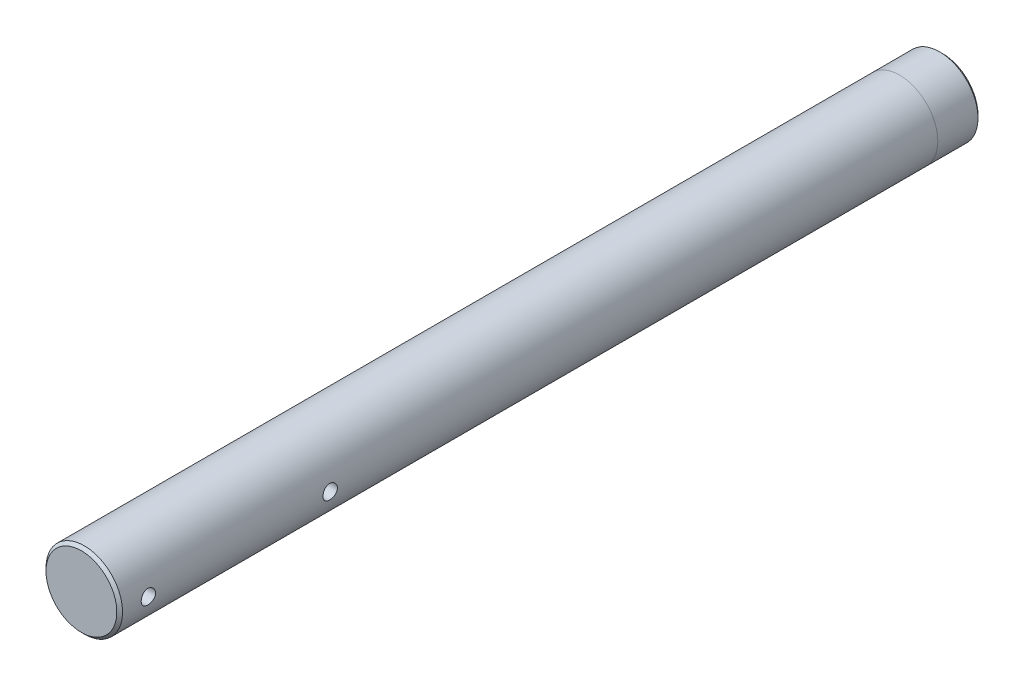
SolidWorks part; units mm, degrees
material "7075-T6, Plate (SS)"
ref_plane "Front" through (0, 0, 0) normal (0, 0, 1) x (1, 0, 0)
ref_plane "Top" through (0, 0, 0) normal (0, 1, 0) x (1, 0, 0)
ref_plane "Right" through (0, 0, 0) normal (1, 0, 0) x (0, 0, -1)
sketch "Sketch1" plane through (0, 0, 0) normal (1, 0, 0) x (0, 0, -1)
  line L0 (0, 4) -> (0, 0) construction
  line L1 (0, 0) -> (59.0815, 0) construction
  line L3 (-45, 4) -> (45, 4)
  line L4 (-45, 4) -> (-45, 0)
  line L5 (-45, 0) -> (45, 0)
  line L6 (45, 4) -> (45, 0)
  dimension "D1" = 8
  dimension "D2" = 90
revolve "Revolve1" add sketch "Sketch1" angle 360 about L1
chamfer "Chamfer1" distance 0.3 angle 45 2 edges at (4, 0, -45) (4, 0, 45)
sketch "Sketch6" plane through (0, 0, 0) normal (1, 0, 0) x (0, 0, -1)
  line L0 (45, 0) -> (-45, 0) construction
  line L1 (45, -3.7) -> (45, 3.7) construction
  line L2 (-45, 3.7) -> (-45, -3.7) construction
  circle A2 centre (-23, 0) radius 0.75
  circle A3 centre (-42, 0) radius 0.75
  dimension "D1" = 1.5
  dimension "D2" = 22
  dimension "D5" = 3
extrude "Cut-Extrude1" cut sketch "Sketch6" against normal through all both and the other way through all
sketch "Sketch7" plane through (0, 0, 0) normal (1, 0, 0) x (0, 0, -1)
  line L0 (40.5, 13.1688) -> (40.5, -9.2412)
  line L1 (45, -3.7) -> (45, 3.7) construction
  dimension "D1" = 4.5
split line "Split Line1"
cosmetic thread "Cosmetic Thread1" parameters "D1"=6, "D2"=6.619
